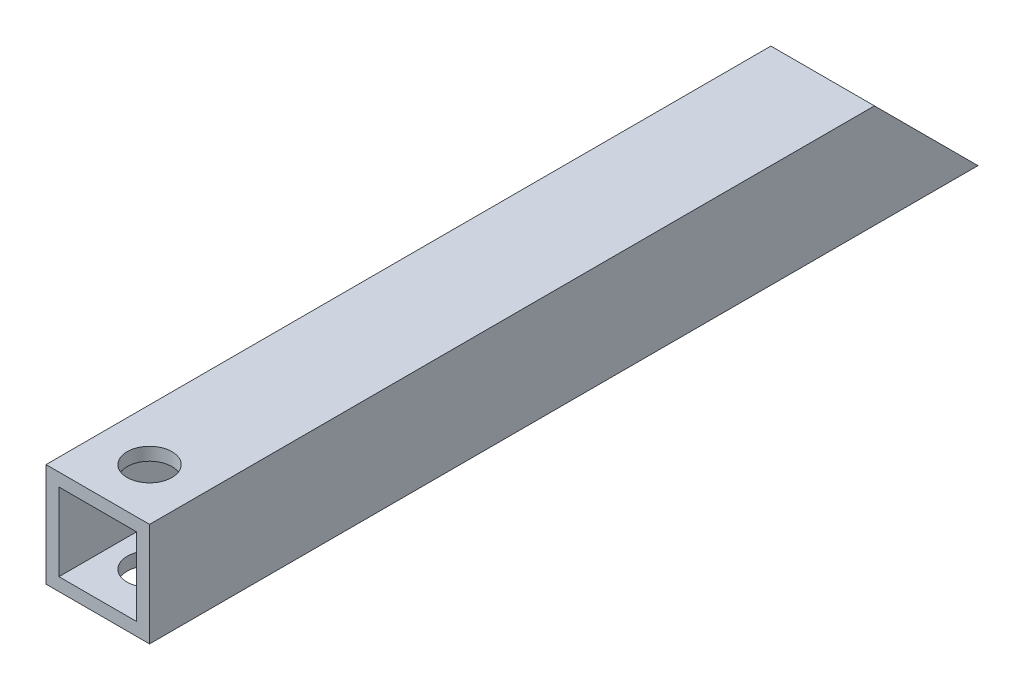
SolidWorks part; units mm, degrees
ref_plane "Front Plane" through (0, 0, 0) normal (0, 0, 1) x (1, 0, 0)
ref_plane "Top Plane" through (0, 0, 0) normal (0, 1, 0) x (1, 0, 0)
ref_plane "Right Plane" through (0, 0, 0) normal (1, 0, 0) x (0, 0, -1)
sketch "Sketch1" plane through (0, 0, 0) normal (0, 0, 1) x (1, 0, 0)
  line L0 (9.525, 9.525) -> (-9.525, 9.525)
  line L1 (12.7, -12.7) -> (-12.7, -12.7)
  line L2 (12.7, -12.7) -> (12.7, 12.7)
  line L3 (12.7, 12.7) -> (-12.7, 12.7)
  line L4 (-12.7, -12.7) -> (-12.7, 12.7)
  line L5 (12.7, -12.7) -> (-12.7, 12.7) construction
  line L6 (12.7, 12.7) -> (-12.7, -12.7) construction
  line L7 (-9.525, -9.525) -> (-9.525, 9.525)
  line L8 (9.525, -9.525) -> (-9.525, -9.525)
  line L9 (9.525, -9.525) -> (9.525, 9.525)
  point P0 (0, 0)
  dimension "D1" = 25.4
  dimension "D2" = 25.4
  dimension "D3" = 3.175
extrude "Boss-Extrude1" add sketch "Sketch1" along normal blind 203.2
sketch "Sketch2" plane through (12.7, 0, 0) normal (1, 0, 0) x (0, 0, -1)
  line L0 (0, 12.7) -> (0, -12.7)
  line L1 (0, -12.7) -> (-25.4, 12.7)
  line L2 (-203.2, 12.7) -> (0, 12.7) construction
  line L3 (-25.4, 12.7) -> (0, 12.7)
  line L4 (-203.2, -12.7) -> (0, -12.7) construction
  dimension "D1" = 45
extrude "Cut-Extrude1" cut sketch "Sketch2" against normal through all
sketch "Sketch3" plane through (0, -12.7, 0) normal (0, -1, 0) x (1, 0, 0)
  line L0 (-12.7, 203.2) -> (12.7, 203.2) construction
  point P0 (0, 190.5)
  point P3 (0, 190.5)
  dimension "D1" = 12.7
sketch "Sketch4" plane through (0, -12.7, 0) normal (0, -1, 0) x (-1, 0, 0)
  point P0 (0, -190.5)
hole_wizard "M10 Clearance Hole1" positions "Sketch4" profile "Sketch5" hole size "M10" standard "ANSI Metric" end condition through all
sketch "Sketch5" plane through (0, -12.7, 190.5) normal (1, 0, 0) x (0, 0, -1)
  line L0 (0, 0) -> (0, 25.4)
  line L1 (0, 25.4) -> (5.5, 25.4)
  line L2 (5.5, 25.4) -> (5.5, 0)
  line L5 (5.5, 0) -> (0, 0)
  line L11 (0, -6.35) -> (0, 107.95) construction
  dimension "Thru Hole Dia." = 11
  dimension "Thru Hole Depth" = 25.4
